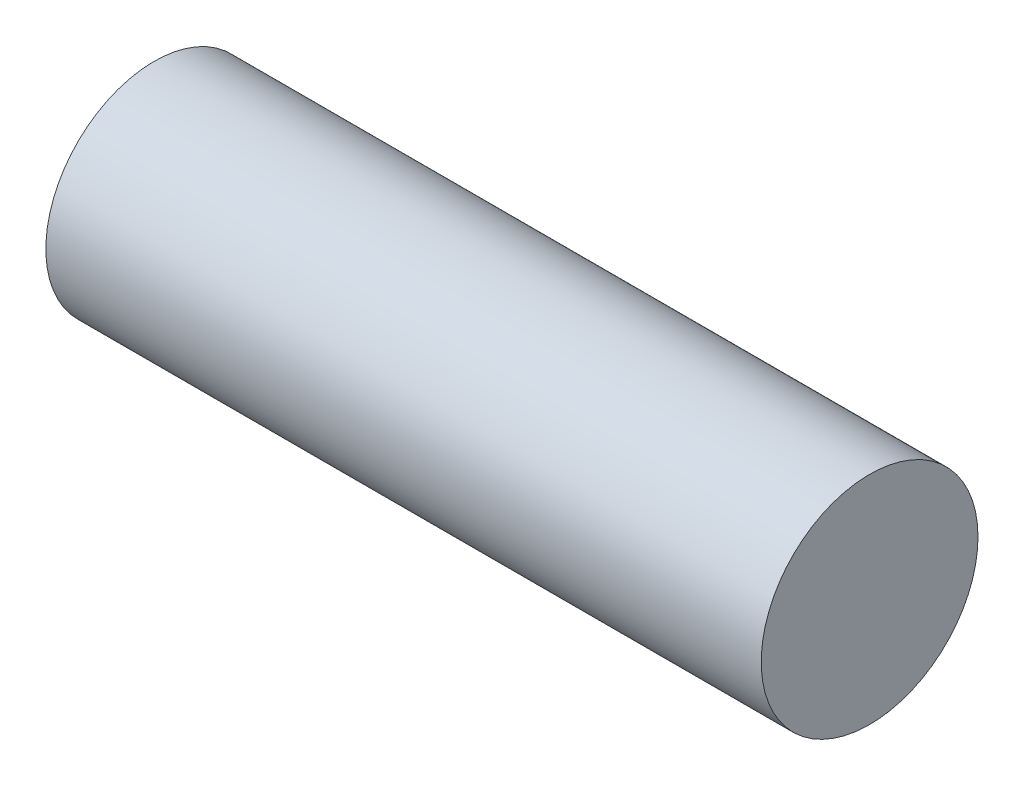
SolidWorks part; units mm, degrees
ref_plane "정면" through (0, 0, 0) normal (0, 0, 1) x (1, 0, 0)
ref_plane "윗면" through (0, 0, 0) normal (0, 1, 0) x (1, 0, 0)
ref_plane "우측면" through (0, 0, 0) normal (1, 0, 0) x (0, 0, -1)
sketch "Sketch1" plane through (0, 0, 0) normal (1, 0, 0) x (0, 0, -1)
  circle A0 centre (0, 0) radius 5
  dimension "D1" = 10
extrude "Boss-Extrude1" add sketch "Sketch1" along normal blind 33
